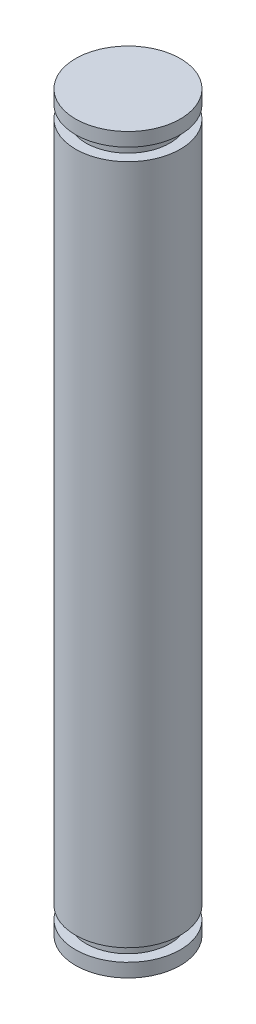
SolidWorks part; units mm, degrees
ref_plane "前视基准面" through (0, 0, 0) normal (0, 0, 1) x (1, 0, 0)
ref_plane "上视基准面" through (0, 0, 0) normal (0, 1, 0) x (1, 0, 0)
ref_plane "右视基准面" through (0, 0, 0) normal (1, 0, 0) x (0, 0, -1)
sketch "草图1" plane through (0, 0, 0) normal (0, 0, 1) x (1, 0, 0)
  line L0 (0, 0) -> (-5, 0)
  line L2 (-5, 70) -> (0, 70)
  line L3 (0, 70) -> (0, 0) construction
  line L4 (-5, 0) -> (-5, 1.3)
  line L5 (-5, 1.3) -> (-4, 1.3)
  line L6 (-4, 1.3) -> (-4, 2.5)
  line L7 (-4, 2.5) -> (-5, 2.5)
  line L8 (-5, 2.5) -> (-5, 67.5)
  line L9 (-5, 67.5) -> (-4, 67.5)
  line L10 (-4, 67.5) -> (-4, 68.7)
  line L11 (-4, 68.7) -> (-5, 68.7)
  line L12 (-5, 68.7) -> (-5, 70)
  line L13 (0, 0) -> (0, 70)
  dimension "D1" = 70
  dimension "D2" = 65
  dimension "D3" = 1.2
  dimension "D4" = 1
  dimension "D5" = 5
revolve "旋转1" add sketch "草图1" angle 360 about L3
